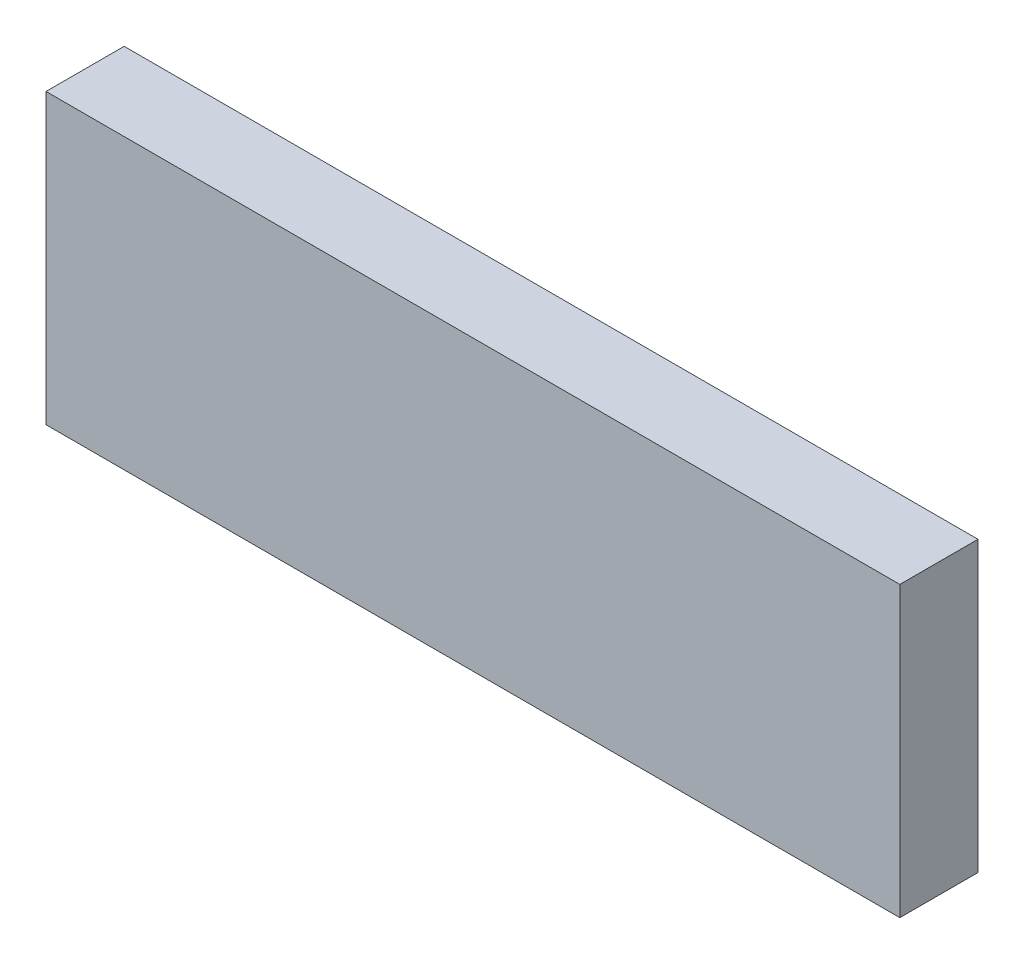
SolidWorks part; units mm, degrees
ref_plane "Front Plane" through (0, 0, 0) normal (0, 0, 1) x (1, 0, 0)
ref_plane "Top Plane" through (0, 0, 0) normal (0, 1, 0) x (1, 0, 0)
ref_plane "Right Plane" through (0, 0, 0) normal (1, 0, 0) x (0, 0, -1)
sketch "Sketch1" plane through (0, 0, 0) normal (0, 0, 1) x (1, 0, 0)
  line L1 (0, 0) -> (142, 0)
  line L2 (0, 0) -> (0, 48)
  line L3 (0, 48) -> (142, 48)
  line L4 (142, 0) -> (142, 48)
  dimension "D1" = 142
  dimension "D2" = 48
extrude "Boss-Extrude1" add sketch "Sketch1" along normal blind 13
